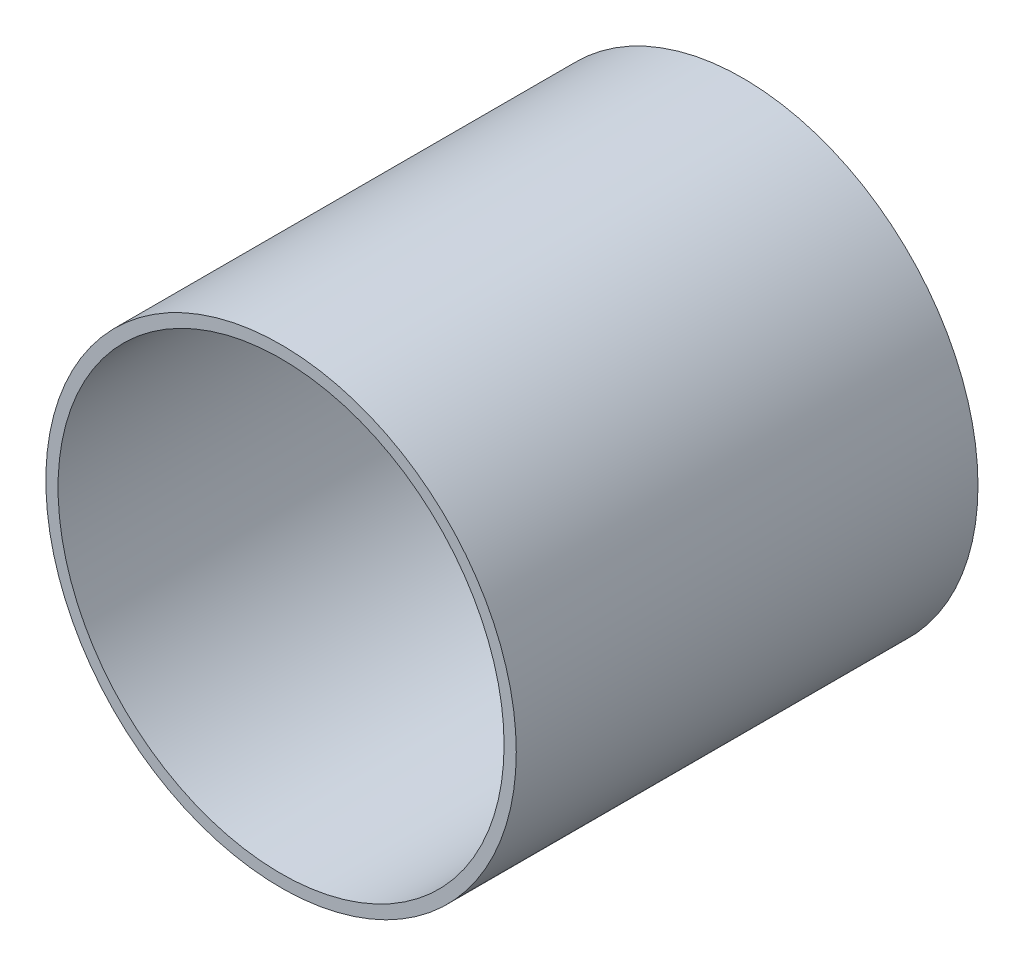
SolidWorks part; units mm, degrees
ref_plane "Front Plane" through (0, 0, 0) normal (0, 0, 1) x (1, 0, 0)
ref_plane "Top Plane" through (0, 0, 0) normal (0, 1, 0) x (1, 0, 0)
ref_plane "Right Plane" through (0, 0, 0) normal (1, 0, 0) x (0, 0, -1)
sketch "Sketch1" plane through (0, 0, 0) normal (0, 0, 1) x (1, 0, 0)
  circle A0 centre (0, 0) radius 27
  dimension "D1" = 54
extrude "Boss-Extrude1" add sketch "Sketch1" along normal blind 53
shell "Shell3" thickness 1.4
